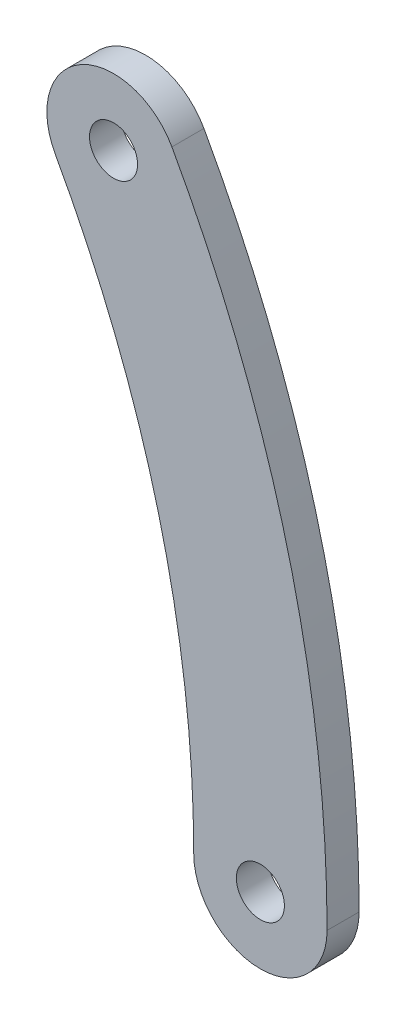
SolidWorks part; units mm, degrees
ref_plane "Piano frontale" through (0, 0, 0) normal (0, 0, 1) x (1, 0, 0)
ref_plane "Piano superiore" through (0, 0, 0) normal (0, 1, 0) x (1, 0, 0)
ref_plane "Piano destro" through (0, 0, 0) normal (1, 0, 0) x (0, 0, -1)
sketch "Schizzo1" plane through (0, 0, 0) normal (0, 0, 1) x (1, 0, 0)
  line L0 (110, 0) -> (96.25, 53.2535) construction
  arc A1 (110, 0) -> (96.25, 53.2535) centre (0, 0) ccw construction
  arc A2 (116.2443, 0) -> (101.7137, 56.2765) centre (0, 0) ccw
  arc A3 (103.7557, 0) -> (90.7863, 50.2305) centre (0, 0) ccw
  arc A4 (103.7557, 0) -> (116.2443, 0) centre (110, 0) ccw
  arc A5 (101.7137, 56.2765) -> (90.7863, 50.2305) centre (96.25, 53.2535) ccw
  point P6 (106.507, 27.5)
extrude "Estrusione-Estrusione1" add sketch "Schizzo1" along normal blind 3
sketch "Schizzo2" plane through (0, 0, 0) normal (0, 0, -1) x (-1, 0, 0)
  circle A0 centre (-110, 0) radius 2.25
  circle A1 centre (-96.25, 53.2535) radius 2.25
  dimension "D1" = 4.5
  dimension "D2" = 4.5
extrude "Taglio-Estrusione1" cut sketch "Schizzo2" against normal through all
